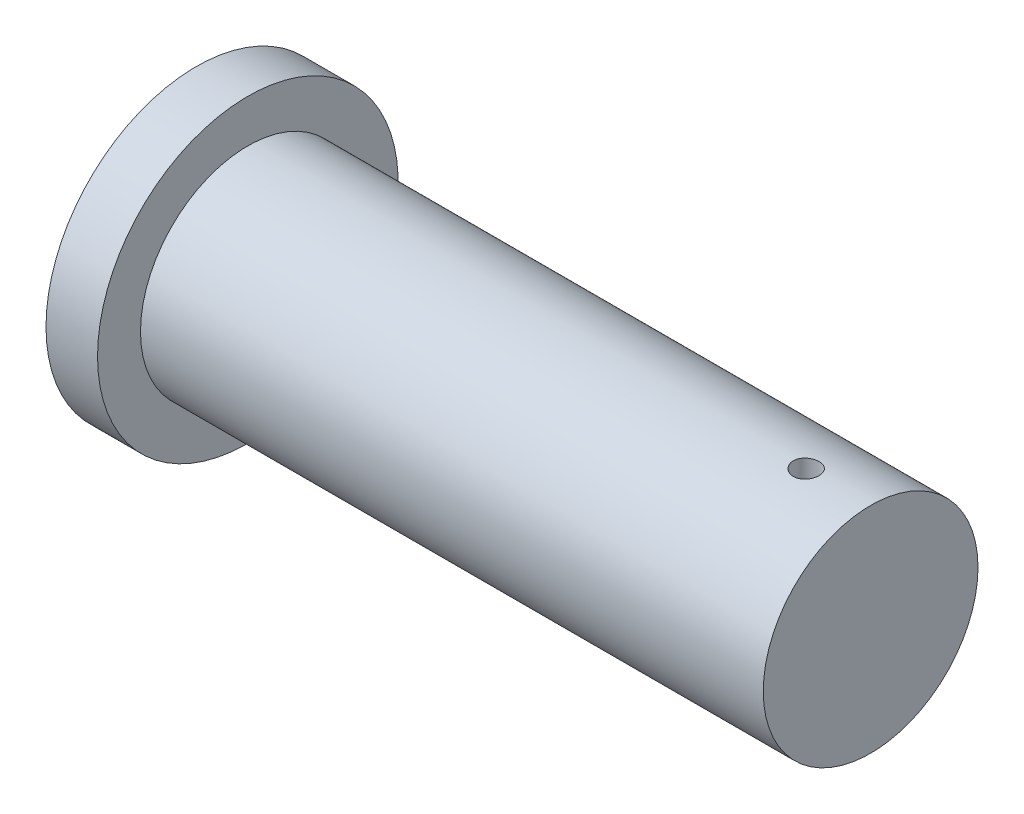
SolidWorks part; units mm, degrees
ref_plane "Front Plane" through (0, 0, 0) normal (0, 0, 1) x (1, 0, 0)
ref_plane "Top Plane" through (0, 0, 0) normal (0, 1, 0) x (1, 0, 0)
ref_plane "Right Plane" through (0, 0, 0) normal (1, 0, 0) x (0, 0, -1)
sketch "Sketch1" plane through (0, 0, 0) normal (0, 0, 1) x (1, 0, 0)
  line L0 (0, 0) -> (0, 25)
  line L1 (0, 25) -> (-145, 25)
  line L2 (-145, 25) -> (-145, 35)
  line L3 (-145, 35) -> (-157, 35)
  line L4 (-157, 35) -> (-157, 0)
  line L5 (-157, 0) -> (0, 0)
  dimension "D1" = 25
  dimension "D2" = 157
  dimension "D3" = 12
  dimension "D4" = 35
revolve "Revolve1" add sketch "Sketch1" angle 360 about L5
sketch "Sketch2" plane through (0, 0, 0) normal (0, 1, 0) x (1, 0, 0)
  line L0 (-145, -35) -> (-145, 35) construction
  line L1 (-145, -25) -> (-145, 25) construction
  line L2 (-145, -25) -> (-145, 25)
  circle A0 centre (-15, 0) radius 3
  dimension "D1" = 6
  dimension "D2" = 130
extrude "Cut-Extrude1" cut sketch "Sketch2" against normal through all both and the other way through all contours A0
